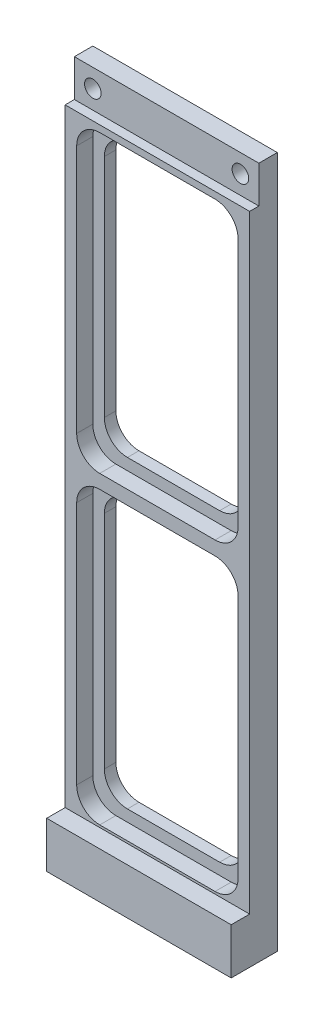
SolidWorks part; units mm, degrees
ref_plane "正面" through (0, 0, 0) normal (0, 0, 1) x (1, 0, 0)
ref_plane "平面" through (0, 0, 0) normal (0, 1, 0) x (1, 0, 0)
ref_plane "右側面" through (0, 0, 0) normal (1, 0, 0) x (0, 0, -1)
sketch "ｽｹｯﾁ1" plane through (0, 0, 0) normal (0, 0, 1) x (1, 0, 0)
  line L1 (0, 0) -> (40, 0)
  line L2 (0, 0) -> (0, 150)
  line L3 (0, 150) -> (40, 150)
  line L4 (40, 0) -> (40, 150)
  dimension "D1" = 150
  dimension "D2" = 40
extrude "ﾎﾞｽ - 押し出し1" add sketch "ｽｹｯﾁ1" along normal blind 6
sketch "ｽｹｯﾁ3" plane through (0, 0, 6) normal (0, 0, 1) x (1, 0, 0)
  line L0 (20, 150) -> (20, 0) construction
  line L1 (40, 150) -> (0, 150) construction
  line L2 (0, 0) -> (40, 0) construction
  line L3 (0, 75) -> (40, 75) construction
  line L4 (0, 150) -> (0, 0) construction
  line L5 (40, 0) -> (40, 150) construction
  line L7 (5, 138) -> (35, 138)
  line L8 (5, 138) -> (5, 79)
  line L9 (5, 79) -> (35, 79)
  line L10 (35, 138) -> (35, 79)
  line L11 (5, 138) -> (35, 79) construction
  line L12 (5, 79) -> (35, 138) construction
  line L13 (5, 71) -> (35, 71)
  line L14 (5, 71) -> (5, 13)
  line L15 (5, 13) -> (35, 13)
  line L16 (35, 71) -> (35, 13)
  line L17 (5, 71) -> (35, 13) construction
  line L18 (5, 13) -> (35, 71) construction
  point P12 (20, 108.5)
  point P17 (20, 42)
  dimension "D1" = 4
  dimension "D2" = 4
  dimension "D3" = 13
  dimension "D4" = 12
  dimension "D5" = 30
extrude "ｶｯﾄ - 押し出し2" cut sketch "ｽｹｯﾁ3" against normal through all
sketch "ｽｹｯﾁ4" plane through (0, 0, 6) normal (0, 0, 1) x (1, 0, 0)
  line L0 (35, 138) -> (5, 138) construction
  line L3 (2.5, 140.5) -> (37.5, 140.5)
  line L6 (2.5, 140.5) -> (2.5, 76.5)
  line L11 (2.5, 76.5) -> (37.5, 76.5)
  line L12 (37.5, 140.5) -> (37.5, 76.5)
  line L17 (2.5, 73.5) -> (37.5, 73.5)
  line L18 (2.5, 73.5) -> (2.5, 10.5)
  line L19 (2.5, 10.5) -> (37.5, 10.5)
  line L20 (37.5, 73.5) -> (37.5, 10.5)
  line L21 (40, 0) -> (40, 150) construction
  line L22 (0, 150) -> (0, 0) construction
  line L24 (5, 79) -> (35, 79) construction
  line L25 (35, 71) -> (5, 71) construction
  line L26 (35, 13) -> (35, 71) construction
  line L27 (5, 13) -> (35, 13) construction
  dimension "D1" = 2.5
  dimension "D2" = 2.5
  dimension "D3" = 2.5
  dimension "D4" = 2.5
  dimension "D5" = 2.5
  dimension "D6" = 2.5
  dimension "D7" = 2.5
  dimension "D8" = 2.5
  dimension "D9" = 59
  dimension "D10" = 58
extrude "ｶｯﾄ - 押し出し3" cut sketch "ｽｹｯﾁ4" against normal blind 3.5
sketch "ｽｹｯﾁ5" plane through (0, 0, 6) normal (0, 0, 1) x (1, 0, 0)
  line L5 (40, 0) -> (40, 150) construction
  line L7 (0, 150) -> (40, 150)
  line L8 (0, 150) -> (0, 141.95)
  line L9 (0, 141.95) -> (40, 141.95)
  line L10 (40, 150) -> (40, 141.95)
  line L11 (4, 146) -> (36.3714, 146) construction
  line L15 (40, 150) -> (0, 150) construction
  dimension "D1" = 4.05
  dimension "D2" = 4
fillet "ﾌｨﾚｯﾄ2" radius 5 16 edges at (37.5, 140.5, 4.25) (2.5, 140.5, 4.25) (35, 79, 1.25) (37.5, 76.5, 4.25) (2.5, 76.5, 4.25) (5, 79, 1.25) (37.5, 73.5, 4.25) (2.5, 73.5, 4.25) (2.5, 10.5, 4.25) (37.5, 10.5, 4.25) (35, 13, 1.25) (5, 13, 1.25) (5, 71, 1.25) (35, 71, 1.25) (35, 138, 1.25) (5, 138, 1.25)
sketch "ｽｹｯﾁ7" plane through (0, 0, 6) normal (0, 0, 1) x (1, 0, 0)
  line L0 (40, 0) -> (40, 150) construction
  line L1 (0, 0) -> (40, 0)
  line L2 (0, 0) -> (0, 9.9987)
  line L3 (0, 9.9987) -> (40, 9.9987)
  line L4 (40, 0) -> (40, 9.9987)
extrude "ﾎﾞｽ - 押し出し2" add sketch "ｽｹｯﾁ7" along normal blind 4
extrude "ｶｯﾄ - 押し出し4" cut sketch "ｽｹｯﾁ5" against normal blind 2
sketch "ｽｹｯﾁ8" plane through (0, 0, 0) normal (0, -1, 0) x (1, 0, 0)
  line L0 (0, 6) -> (40, 6) construction
  line L1 (40, 10) -> (40, 0) construction
  line L4 (0, 10) -> (40, 10) construction
  line L5 (0, 10) -> (0, 0) construction
  circle A0 centre (5, 6) radius 2.4
  circle A1 centre (25, 6) radius 2.4
  circle A2 centre (35, 6) radius 2.4
  circle A3 centre (15, 6) radius 2.4
  dimension "D1" = 4.8
  dimension "D2" = 4
  dimension "D3" = 5
  dimension "D4" = 20
  dimension "D5" = 5
  dimension "D6" = 20
extrude "ｶｯﾄ - 押し出し5" cut sketch "ｽｹｯﾁ8" against normal blind 6
sketch "ｽｹｯﾁ9" plane through (0, 0, 4) normal (0, 0, 1) x (1, 0, 0)
  line L0 (0, 146) -> (40, 146) construction
  line L1 (0, 150) -> (0, 141.95) construction
  line L2 (40, 141.95) -> (40, 150) construction
  line L3 (40, 150) -> (0, 150) construction
  circle A0 centre (4, 146) radius 1.8
  circle A1 centre (36, 146) radius 1.8
  dimension "D4" = 3.6
  dimension "D1" = 4
  dimension "D2" = 4
  dimension "D3" = 4
extrude "ｶｯﾄ - 押し出し6" cut sketch "ｽｹｯﾁ9" against normal through all
